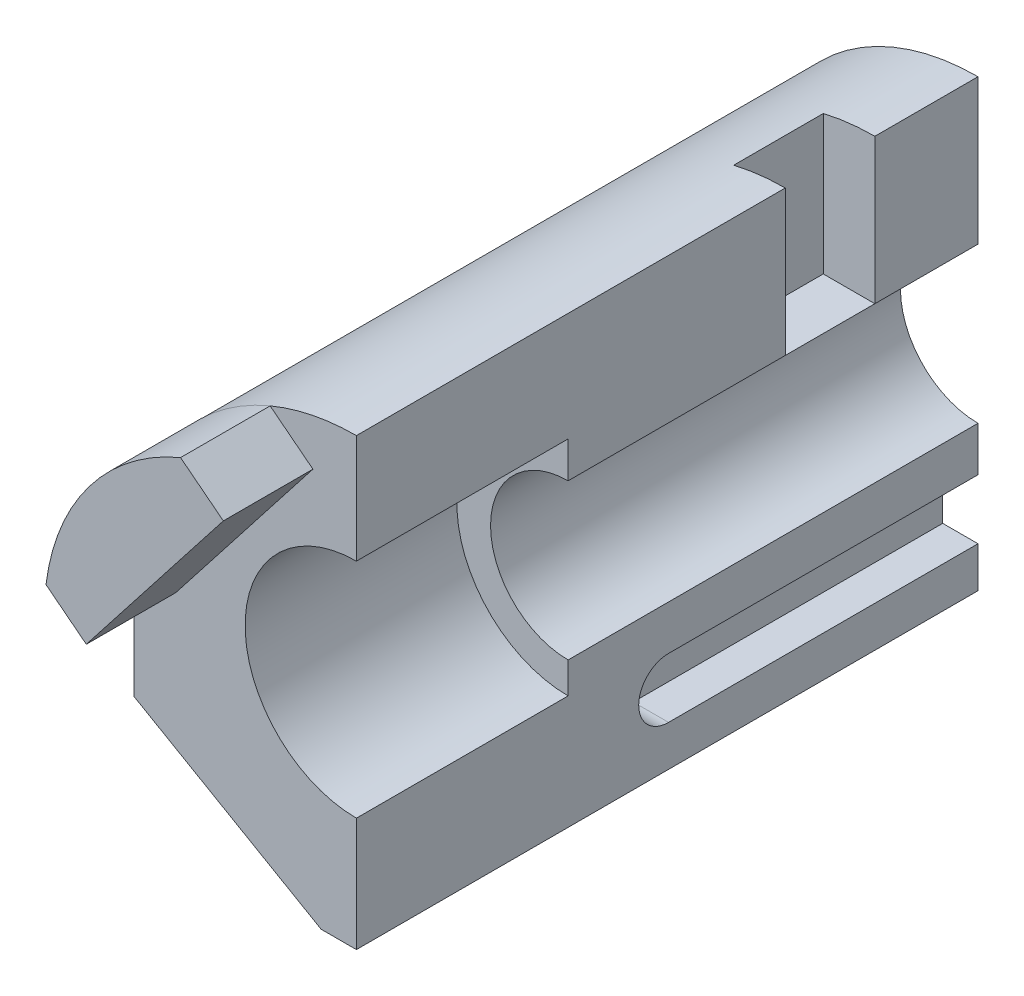
SolidWorks part; units mm, degrees
material "1060 Alloy"
ref_plane "Front Plane" through (0, 0, 0) normal (0, 0, 1) x (1, 0, 0)
ref_plane "Top Plane" through (0, 0, 0) normal (0, 1, 0) x (1, 0, 0)
ref_plane "Right Plane" through (0, 0, 0) normal (1, 0, 0) x (0, 0, -1)
sketch "Sketch1" plane through (0, 0, 0) normal (0, 0, 1) x (1, 0, 0)
  line L0 (0, 42.1628) -> (0, 0)
  line L1 (0, 0) -> (69, -39.8372)
  line L2 (69, -39.8372) -> (82, -39.8372)
  line L3 (82, -39.8372) -> (82, 13.5878)
  line L4 (82, 70.7378) -> (82, 124.1628)
  arc A1 (82, 13.5878) -> (82, 70.7378) centre (82, 42.1628) cw
  arc A2 (0, 42.1628) -> (82, 124.1628) centre (82, 42.1628) cw
  point P11 (81.8346, 108.824)
  dimension "D1" = 30
  dimension "D4" = 82
  dimension "D6" = 28.575
  dimension "D2" = 13
  dimension "D3" = 82
  dimension "D5" = 82
  dimension "D7" = 82
extrude "Boss-Extrude1" add sketch "Sketch1" along normal blind 229
sketch "Sketch2" plane through (0, 0, 229) normal (0, 0, 1) x (1, 0, 0)
  line L0 (50.219, 117.7536) -> (65.9792, 105.4404)
  line L1 (65.9792, 105.4404) -> (15.495, 40.8235)
  line L2 (15.495, 40.8235) -> (0.6448, 52.4257)
  line L4 (69, -39.8372) -> (82, -39.8372) construction
  arc A0 (82, 124.1628) -> (0, 42.1628) centre (82, 42.1628) ccw construction
  arc A1 (0.6448, 52.4257) -> (50.219, 117.7536) centre (81.5362, 42.5148) cw
  dimension "D1" = 82
  dimension "D2" = 51
  dimension "D3" = 38
  dimension "D4" = 20
  dimension "D5" = 40
extrude "Boss-Extrude3" add sketch "Sketch2" along normal blind 33
sketch "Sketch3" plane through (0, 0, 229) normal (0, 0, 1) x (1, 0, 0)
  line L0 (82, 84.1084) -> (82, 2.1084)
  line L1 (82, 70.7378) -> (82, 124.1628) construction
  line L2 (82, -39.8372) -> (82, 13.5878) construction
  line L3 (15.495, 40.8235) -> (65.9792, 105.4404) construction
  arc A0 (82, 84.1084) -> (82, 2.1084) centre (82, 43.1084) ccw
  dimension "D1" = 41
  dimension "D2" = 51
extrude "Cut-Extrude1" cut sketch "Sketch3" against normal blind 78
sketch "Sketch4" plane through (82, 0, 0) normal (1, 0, 0) x (0, 0, -1)
  line L0 (-229, 124.1628) -> (0, 124.1628) construction
  line L1 (-71, 124.1628) -> (-38, 124.1628)
  line L2 (-71, 124.1628) -> (-71, 70.7378)
  line L3 (-71, 70.7378) -> (-38, 70.7378)
  line L4 (-38, 124.1628) -> (-38, 70.7378)
  line L5 (-151, 70.7378) -> (0, 70.7378) construction
  dimension "D1" = 33
  dimension "D2" = 38
extrude "Cut-Extrude2" cut sketch "Sketch4" against normal blind 19
sketch "Sketch5" plane through (82, 0, 0) normal (1, 0, 0) x (0, 0, -1)
  line L0 (0, -13.8372) -> (-114, -13.8372) construction
  line L1 (0, -39.8372) -> (0, 13.5878) construction
  line L2 (0, -24.8372) -> (-114, -24.8372)
  line L3 (0, -2.8372) -> (-114, -2.8372)
  arc A0 (0, -24.8372) -> (0, -2.8372) centre (0, -13.8372) ccw
  arc A1 (-114, -2.8372) -> (-114, -24.8372) centre (-114, -13.8372) ccw
  point P4 (-57, -13.8372)
  dimension "D2" = 11
  dimension "D3" = 26
  dimension "D1" = 114
extrude "Cut-Extrude3" cut sketch "Sketch5" against normal blind 13
equation "\"a\"= 229"
equation "\"b\"= 114"
equation "\"c\"= 82"
